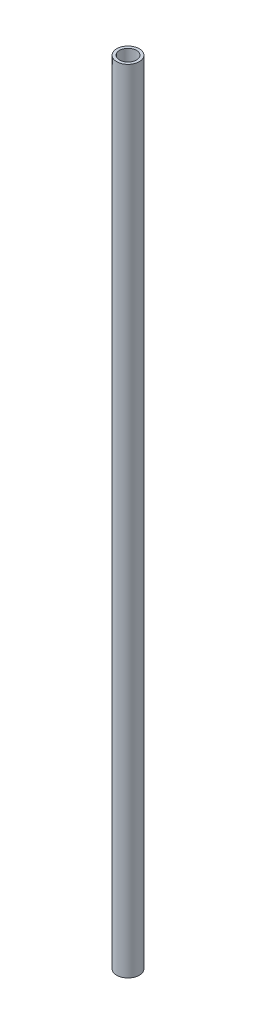
SolidWorks part; units mm, degrees
material "Acrylic (Medium-high impact)"
ref_plane "Front Plane" through (0, 0, 0) normal (0, 0, 1) x (1, 0, 0)
ref_plane "Top Plane" through (0, 0, 0) normal (0, 1, 0) x (1, 0, 0)
ref_plane "Right Plane" through (0, 0, 0) normal (1, 0, 0) x (0, 0, -1)
sketch "Sketch1" plane through (0, 0, 0) normal (0, 1, 0) x (1, 0, 0)
  circle A0 centre (0, 0) radius 6.35
  circle A1 centre (0, 0) radius 4.7625
  dimension "D1" = 1.5875
  dimension "D2" = 12.7
extrude "Boss-Extrude1" add sketch "Sketch1" along normal blind 446.2018
